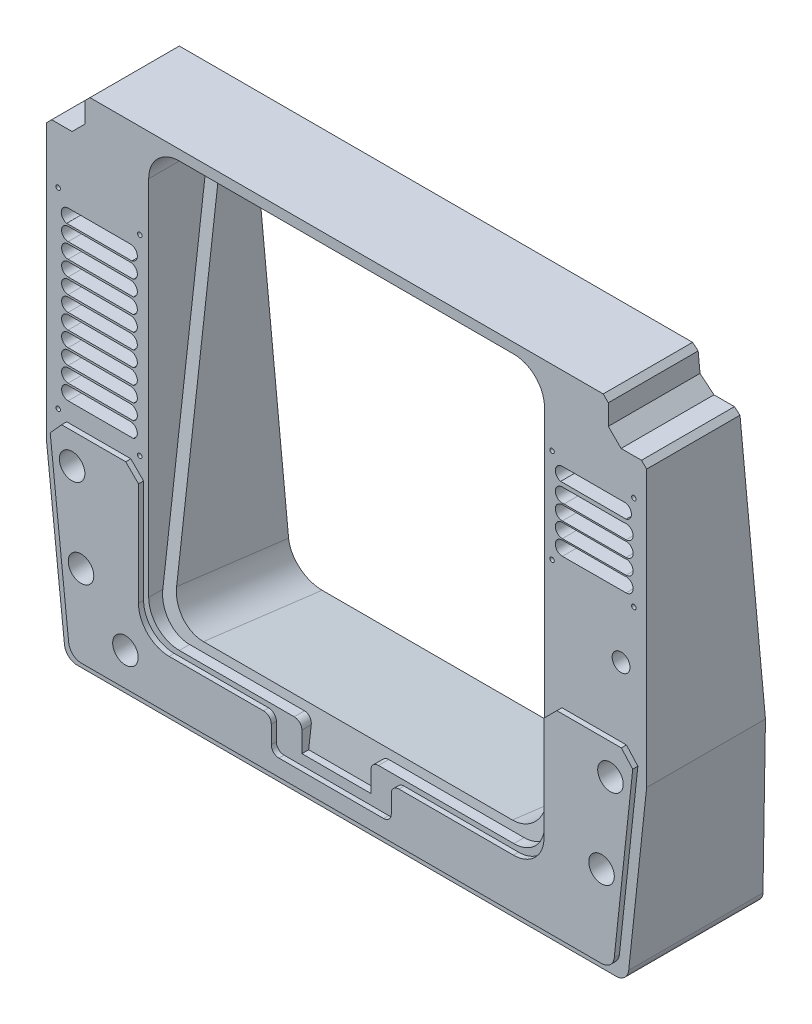
SolidWorks part; units mm, degrees
ref_plane "Front Plane" through (0, 0, 0) normal (0, 0, 1) x (1, 0, 0)
ref_plane "Top Plane" through (0, 0, 0) normal (0, 1, 0) x (1, 0, 0)
ref_plane "Right Plane" through (0, 0, 0) normal (1, 0, 0) x (0, 0, -1)
sketch "Sketch1" plane through (0, 0, 0) normal (0, 0, 1) x (1, 0, 0)
  line L0 (177.8192, -40.4681) -> (170.3192, -110.4681)
  line L1 (-40.1808, 84.5319) -> (160.8192, 84.5319)
  line L2 (-57.1808, 67.5319) -> (-57.1808, -40.4681)
  line L3 (-49.6808, -110.4681) -> (170.3192, -110.4681)
  line L4 (177.8192, 67.5319) -> (177.8192, -40.4681)
  line L5 (-57.1808, -40.4681) -> (-49.6808, -110.4681)
  line L6 (-42.1808, 74.5319) -> (-47.1808, 69.5319)
  line L8 (-42.1808, 82.5319) -> (-42.1808, 74.5319)
  line L9 (-47.1808, 69.5319) -> (-55.1808, 69.5319)
  line L13 (175.8192, 69.5319) -> (167.8192, 69.5319)
  line L14 (162.8192, 82.5319) -> (162.8192, 74.5319)
  line L15 (162.8192, 74.5319) -> (167.8192, 69.5319)
  line L16 (160.8192, 84.5319) -> (162.8192, 82.5319)
  line L17 (177.8192, 67.5319) -> (175.8192, 69.5319)
  line L18 (-55.1808, 69.5319) -> (-57.1808, 67.5319)
  line L19 (-40.1808, 84.5319) -> (-42.1808, 82.5319)
  point P1 (-42.1808, 84.5319)
  point P2 (-57.1808, 69.5319)
  point P4 (-57.1808, -40.4681)
  point P5 (177.8192, -40.4681)
  point P10 (-42.1808, 69.5319)
  point P11 (162.8192, 69.5319)
  point P12 (177.8192, 69.5319)
  point P13 (162.8192, 84.5319)
  dimension "D2" = 70
  dimension "D3" = 70
  dimension "D4" = 220
  dimension "D5" = 15
  dimension "D6" = 15
  dimension "D7" = 15
  dimension "D8" = 15
extrude "Boss-Extrude1" add sketch "Sketch1" along normal blind 53
sketch "Sketch2" plane through (0, 0, 53) normal (0, 0, 1) x (1, 0, 0)
  line L0 (160.8192, 84.5319) -> (-40.1808, 84.5319) construction
  line L1 (-5.1808, 80.5319) -> (125.8192, 80.5319)
  line L2 (-17.1808, 68.5319) -> (-17.1808, -73.4681)
  line L3 (-5.1808, -85.4681) -> (125.8192, -85.4681)
  line L4 (137.8192, 68.5319) -> (137.8192, -73.4681)
  line L5 (-57.1808, 67.5319) -> (-57.1808, -40.4681) construction
  arc A0 (-17.1808, -73.4681) -> (-5.1808, -85.4681) centre (-5.1808, -73.4681) ccw
  arc A1 (125.8192, -85.4681) -> (137.8192, -73.4681) centre (125.8192, -73.4681) ccw
  arc A2 (137.8192, 68.5319) -> (125.8192, 80.5319) centre (125.8192, 68.5319) ccw
  arc A3 (-5.1808, 80.5319) -> (-17.1808, 68.5319) centre (-5.1808, 68.5319) ccw
  point P10 (-17.1808, -85.4681)
  point P15 (137.8192, 80.5319)
  point P18 (-17.1808, 80.5319)
  dimension "D5" = 12
  dimension "D1" = 155
  dimension "D2" = 166
  dimension "D3" = 4
  dimension "D4" = 40
extrude "Cut-Extrude1" cut sketch "Sketch2" against normal blind 53
sketch "Sketch3" plane through (-17.1808, 0, 0) normal (1, 0, 0) x (0, 0, -1)
  line L0 (-50.9539, -101.3132) -> (-28, 81.8998)
  line L1 (-28, 81.8998) -> (0, 81.8998)
  line L3 (0, -101.3132) -> (-50.9539, -101.3132)
  line L4 (0, 81.8998) -> (0, -101.3132)
  dimension "D1" = 4
  dimension "D2" = 25
extrude "Boss-Extrude2" add sketch "Sketch3" along normal blind 173
sketch "Sketch4" plane through (0, 4.7194, 37.6696) normal (0, 0.1243, 0.9922) x (1, 0, 0)
  line L1 (-0.1808, 70.4051) -> (120.8192, 70.4051)
  line L2 (-12.1808, 58.4051) -> (-12.1808, -75.5949)
  line L3 (-0.1808, -87.5949) -> (120.8192, -87.5949)
  line L4 (132.8192, 58.4051) -> (132.8192, -75.5949)
  line L5 (125.8192, 76.4051) -> (-5.1808, 76.4051) construction
  line L6 (-17.1808, 61.4117) -> (-17.1808, -79.4869) construction
  arc A0 (-12.1808, 58.4051) -> (-0.1808, 70.4051) centre (-0.1808, 58.4051) cw
  arc A1 (132.8192, 58.4051) -> (120.8192, 70.4051) centre (120.8192, 58.4051) ccw
  arc A2 (120.8192, -87.5949) -> (132.8192, -75.5949) centre (120.8192, -75.5949) ccw
  arc A3 (-0.1808, -87.5949) -> (-12.1808, -75.5949) centre (-0.1808, -75.5949) cw
  point P10 (-12.1808, 70.4051)
  point P13 (132.8192, 70.4051)
  point P18 (-12.1808, -87.5949)
  dimension "D5" = 12
  dimension "D1" = 145
  dimension "D2" = 158
  dimension "D3" = 6
  dimension "D4" = 5
extrude "Cut-Extrude2" cut sketch "Sketch4" against normal blind 53
sketch "Sketch6" plane through (0, 0, 53) normal (0, 0, 1) x (1, 0, 0)
  line L0 (-5.1808, -85.4681) -> (125.8192, -85.4681) construction
  line L1 (42.8192, -85.4681) -> (69.8192, -85.4681)
  line L2 (42.8192, -85.4681) -> (42.8192, -96.4681)
  line L3 (42.8192, -96.4681) -> (69.8192, -96.4681)
  line L4 (69.8192, -85.4681) -> (69.8192, -96.4681)
  line L5 (-17.1808, 68.5319) -> (-17.1808, -73.4681) construction
  dimension "D1" = 27
  dimension "D2" = 11
  dimension "D3" = 60
extrude "Cut-Extrude3" cut sketch "Sketch6" against normal up to surface (4.0313 mm away)
fillet "Fillet1" radius 3 2 edges at (69.8192, -85.4681, 50.9844) (42.8192, -85.4681, 50.9844)
fillet "Fillet2" radius 5 2 edges at (170.3192, -110.4681, 26.5) (-49.6808, -110.4681, 26.5)
sketch "Sketch7" plane through (0, 0, 53) normal (0, 0, 1) x (1, 0, 0)
  line L0 (-53.7503, -34.9397) -> (-46.5116, -102.5008)
  line L1 (-41.54, -106.9681) -> (162.1784, -106.9681)
  line L2 (167.1499, -102.5008) -> (174.3886, -34.9397)
  line L3 (169.9213, -29.9681) -> (144.6613, -29.9681)
  line L4 (139.6613, -34.9681) -> (139.6613, -75.4681)
  line L5 (127.6613, -87.4681) -> (82.8192, -87.4681)
  line L6 (79.8192, -90.4681) -> (79.8192, -97.4681)
  line L7 (76.8192, -100.4681) -> (35.8192, -100.4681)
  line L8 (32.8192, -97.4681) -> (32.8192, -90.4681)
  line L9 (29.8192, -87.4681) -> (-7.1808, -87.4681)
  line L10 (-19.1808, -75.4681) -> (-19.1808, -34.9681)
  line L11 (-24.1808, -29.9681) -> (-49.2829, -29.9681)
  line L12 (-45.1879, -110.4681) -> (165.8263, -110.4681) construction
  line L13 (-57.1808, -40.4681) -> (-50.1595, -106.0008) construction
  line L16 (-17.1808, 68.5319) -> (-17.1808, -73.4681) construction
  line L17 (170.7978, -106.0008) -> (177.8192, -40.4681) construction
  line L18 (42.8192, -88.4681) -> (42.8192, -96.4681) construction
  line L19 (69.8192, -96.4681) -> (69.8192, -88.4681) construction
  line L20 (-49.2829, -29.9681) -> (-53.7503, -34.9397)
  line L21 (-19.1808, -34.9681) -> (-24.1808, -29.9681)
  line L22 (144.6613, -29.9681) -> (139.6613, -34.9681)
  line L23 (174.3886, -34.9397) -> (169.9213, -29.9681)
  line L25 (-5.1808, -85.4681) -> (39.8192, -85.4681) construction
  line L26 (72.8192, -85.4681) -> (125.8192, -85.4681) construction
  arc A0 (-41.54, -106.9681) -> (-46.5116, -102.5008) centre (-41.54, -101.9681) cw
  arc A1 (167.1499, -102.5008) -> (162.1784, -106.9681) centre (162.1784, -101.9681) cw
  arc A2 (-19.1808, -75.4681) -> (-7.1808, -87.4681) centre (-7.1808, -75.4681) ccw
  arc A3 (127.6613, -87.4681) -> (139.6613, -75.4681) centre (127.6613, -75.4681) ccw
  arc A4 (76.8192, -100.4681) -> (79.8192, -97.4681) centre (76.8192, -97.4681) ccw
  arc A5 (79.8192, -90.4681) -> (82.8192, -87.4681) centre (82.8192, -90.4681) cw
  arc A6 (35.8192, -100.4681) -> (32.8192, -97.4681) centre (35.8192, -97.4681) cw
  arc A7 (32.8192, -90.4681) -> (29.8192, -87.4681) centre (29.8192, -90.4681) ccw
  point P0 (-54.2829, -29.9681)
  point P4 (174.9213, -29.9681)
  point P5 (139.6613, -29.9681)
  point P12 (-19.1808, -29.9681)
  point P37 (-46.0329, -106.9681)
  point P40 (166.6713, -106.9681)
  dimension "D13" = 5
  dimension "D14" = 5
  dimension "D15" = 12
  dimension "D20" = 3
  dimension "D1" = 77
  dimension "D2" = 77
  dimension "D3" = 3.5
  dimension "D4" = 10
  dimension "D5" = 6.5
  dimension "D6" = 2
  dimension "D7" = 2
  dimension "D8" = 4
  dimension "D9" = 2
  dimension "D10" = 35.26
  dimension "D11" = 10
  dimension "D12" = 4
extrude "Boss-Extrude3" add sketch "Sketch7" along normal blind 2
sketch "Sketch15" plane through (0, 0, 0) normal (0, 0, -1) x (-1, 0, 0)
  circle A0 centre (20.6609, 47.7881) radius 0.875
  circle A1 centre (52.6329, 47.7881) radius 0.875
  circle A2 centre (20.6603, -27.217) radius 0.875
  circle A3 centre (52.6417, -27.217) radius 0.875
  circle A4 centre (-172.8186, 55.216) radius 0.875
  circle A5 centre (-140.7816, 55.216) radius 0.875
  circle A6 centre (-140.7816, 18.277) radius 0.875
  circle A7 centre (-172.8186, 18.277) radius 0.875
  dimension "D1" = 1.75
  dimension "D2" = 1.75
  dimension "D3" = 1.75
  dimension "D4" = 1.75
  dimension "D5" = 1.75
  dimension "D6" = 1.75
  dimension "D7" = 1.75
  dimension "D8" = 1.75
extrude "Cut-Extrude5" cut sketch "Sketch15" along normal blind 15 from surface at -53 starting at face at (60.3192, 21.1446, 53)
sketch "Sketch16" plane through (0, 0, 55) normal (0, 0, 1) x (1, 0, 0)
  line L0 (169.9213, -29.9681) -> (144.6613, -29.9681) construction
  line L1 (139.6613, -34.9681) -> (139.6613, -75.4681) construction
  line L2 (139.6613, -34.9681) -> (139.6613, -75.4681) construction
  line L3 (-41.54, -106.9681) -> (162.1784, -106.9681) construction
  line L4 (-53.7503, -34.9397) -> (-46.5116, -102.5008) construction
  line L5 (-19.1808, -75.4681) -> (-19.1808, -34.9681) construction
  line L6 (-24.1808, -29.9681) -> (-49.2829, -29.9681) construction
  line L7 (137.8192, -73.4681) -> (137.8192, 68.5319) construction
  circle A0 centre (162.1613, -74.9681) radius 5
  circle A1 centre (165.6613, -41.9681) radius 5
  circle A2 centre (-24.2942, -93.9681) radius 5
  circle A3 centre (-41.6808, -74.9681) radius 5
  circle A4 centre (-45.1808, -41.9681) radius 5
  circle A5 centre (167.8192, -2.9681) radius 3.5
  dimension "D3" = 10
  dimension "D6" = 10
  dimension "D9" = 10
  dimension "D14" = 10
  dimension "D15" = 10
  dimension "D18" = 7
  dimension "D1" = 45
  dimension "D2" = 22.5
  dimension "D4" = 12
  dimension "D5" = 26
  dimension "D7" = 13
  dimension "D8" = 23
  dimension "D10" = 22.5
  dimension "D11" = 45
  dimension "D12" = 26
  dimension "D13" = 12
  dimension "D16" = 30
  dimension "D17" = 27
extrude "Cut-Extrude6" cut sketch "Sketch16" against normal blind 60
sketch "Sketch17" plane through (0, 0, 53) normal (0, 0, 1) x (1, 0, 0)
  line L0 (-57.1808, 67.5319) -> (-57.1808, -40.4681) construction
  line L1 (-51.1808, 47.7819) -> (-22.1808, 47.7819)
  line L2 (-54.1808, 47.7819) -> (-54.1808, -27.2181)
  line L3 (-51.1808, -27.2181) -> (-22.1808, -27.2181)
  line L4 (-19.1808, 47.7819) -> (-19.1808, -27.2181)
  line L5 (-68.8168, 10.2819) -> (9.6258, 10.2819) construction
  line L6 (-48.6808, 36.6406) -> (-24.3739, 36.6406)
  line L7 (-48.6808, 42.7819) -> (-24.3708, 42.7819)
  line L9 (-49.2897, 37.3501) -> (-23.762, 37.3501)
  line L10 (-48.7307, 31.4236) -> (-23.1589, 31.4236)
  line L11 (-48.6808, 30.6406) -> (-24.3739, 30.6406)
  line L12 (-48.7307, 25.4236) -> (-23.1589, 25.4236)
  line L13 (-48.6808, 24.6406) -> (-24.3739, 24.6406)
  line L14 (-48.7307, 19.4236) -> (-23.1589, 19.4236)
  line L15 (-48.6808, 18.6406) -> (-24.3739, 18.6406)
  line L16 (-48.7307, 13.4236) -> (-23.1589, 13.4236)
  line L17 (-48.6808, 12.6406) -> (-24.3739, 12.6406)
  line L18 (-48.7307, 7.4236) -> (-23.1589, 7.4236)
  line L19 (-48.6808, 6.6406) -> (-24.3739, 6.6406)
  line L20 (-48.7307, 1.4236) -> (-23.1589, 1.4236)
  line L21 (-48.6808, 0.6406) -> (-24.3739, 0.6406)
  line L22 (-48.7307, -4.5764) -> (-23.1589, -4.5764)
  line L23 (-48.6808, -5.3594) -> (-24.3739, -5.3594)
  line L24 (-48.7307, -10.5764) -> (-23.1589, -10.5764)
  line L25 (-48.6808, -11.3594) -> (-24.3739, -11.3594)
  line L26 (-48.7307, -16.5764) -> (-23.1589, -16.5764)
  line L27 (-48.6837, -17.3594) -> (-24.3768, -17.3594)
  line L28 (-48.7336, -22.5764) -> (-23.1617, -22.5764)
  line L29 (144.8128, 39.542) -> (169.7853, 39.542)
  line L30 (142.3192, 55.2119) -> (171.3192, 55.2119)
  line L31 (139.3192, 55.2119) -> (139.3192, 18.2119)
  line L32 (142.3192, 18.2119) -> (172.7887, 18.2119)
  line L33 (174.3192, 55.2119) -> (174.3192, 16.7122)
  line L34 (-47.1808, 69.5319) -> (-55.1808, 69.5319) construction
  line L35 (144.8192, 51.9619) -> (169.1261, 51.9619)
  line L36 (144.1467, 46.5453) -> (169.7985, 46.5453)
  line L37 (144.8192, 44.9619) -> (169.1261, 44.9619)
  line L38 (144.7932, 44.9617) -> (169.1256, 44.9617)
  line L39 (144.8192, 38.9619) -> (169.1261, 38.9619)
  line L40 (144.7932, 38.9617) -> (169.1256, 38.9617)
  line L41 (144.8192, 32.9619) -> (169.1261, 32.9619)
  line L42 (144.7932, 32.9617) -> (169.1256, 32.9617)
  line L43 (144.8192, 26.9619) -> (169.1261, 26.9619)
  line L44 (144.7932, 26.9617) -> (169.1256, 26.9617)
  line L45 (177.8192, -40.4681) -> (177.8192, 67.5319) construction
  line L46 (169.7853, 33.542) -> (144.8192, 33.4619)
  line L47 (175.8192, 69.5319) -> (167.8192, 69.5319) construction
  line L48 (144.8192, 27.4619) -> (169.7853, 27.542)
  line L49 (144.8192, 21.4619) -> (169.7941, 21.542)
  arc A0 (-51.1808, 47.7819) -> (-54.1808, 47.7819) centre (-52.6808, 47.7819) ccw
  arc A1 (-19.1808, 47.7819) -> (-22.1808, 47.7819) centre (-20.6808, 47.7819) ccw
  arc A2 (-51.1808, -27.2181) -> (-54.1808, -27.2181) centre (-52.6808, -27.2181) cw
  arc A3 (-19.1808, -27.2181) -> (-22.1808, -27.2181) centre (-20.6808, -27.2181) cw
  arc A4 (-23.762, 37.3501) -> (-24.3708, 42.7819) centre (-24.3708, 40.0319) ccw
  arc A5 (-48.6808, 42.7819) -> (-49.2897, 37.3501) centre (-48.6808, 40.0319) ccw
  arc A6 (-23.1589, 31.4236) -> (-24.3739, 36.6406) centre (-24.3739, 33.8906) ccw
  arc A7 (-48.6808, 36.6406) -> (-48.7307, 31.4236) centre (-48.6808, 34.0319) ccw
  arc A8 (-23.1589, 25.4236) -> (-24.3739, 30.6406) centre (-24.3739, 27.8906) ccw
  arc A9 (-48.6808, 30.6406) -> (-48.7307, 25.4236) centre (-48.6808, 28.0319) ccw
  arc A10 (-23.1589, 19.4236) -> (-24.3739, 24.6406) centre (-24.3739, 21.8906) ccw
  arc A11 (-48.6808, 24.6406) -> (-48.7307, 19.4236) centre (-48.6808, 22.0319) ccw
  arc A12 (-23.1589, 13.4236) -> (-24.3739, 18.6406) centre (-24.3739, 15.8906) ccw
  arc A13 (-48.6808, 18.6406) -> (-48.7307, 13.4236) centre (-48.6808, 16.0319) ccw
  arc A14 (-23.1589, 7.4236) -> (-24.3739, 12.6406) centre (-24.3739, 9.8906) ccw
  arc A15 (-48.6808, 12.6406) -> (-48.7307, 7.4236) centre (-48.6808, 10.0319) ccw
  arc A16 (-23.1589, 1.4236) -> (-24.3739, 6.6406) centre (-24.3739, 3.8906) ccw
  arc A17 (-48.6808, 6.6406) -> (-48.7307, 1.4236) centre (-48.6808, 4.0319) ccw
  arc A18 (-23.1589, -4.5764) -> (-24.3739, 0.6406) centre (-24.3739, -2.1094) ccw
  arc A19 (-48.6808, 0.6406) -> (-48.7307, -4.5764) centre (-48.6808, -1.9681) ccw
  arc A20 (-23.1589, -10.5764) -> (-24.3739, -5.3594) centre (-24.3739, -8.1094) ccw
  arc A21 (-48.6808, -5.3594) -> (-48.7307, -10.5764) centre (-48.6808, -7.9681) ccw
  arc A22 (-23.1589, -16.5764) -> (-24.3739, -11.3594) centre (-24.3739, -14.1094) ccw
  arc A23 (-48.6808, -11.3594) -> (-48.7307, -16.5764) centre (-48.6808, -13.9681) ccw
  arc A24 (-23.1617, -22.5764) -> (-24.3768, -17.3594) centre (-24.3768, -20.1094) ccw
  arc A25 (-48.6837, -17.3594) -> (-48.7336, -22.5764) centre (-48.6837, -19.9681) ccw
  arc A26 (169.7985, 46.5453) -> (169.1261, 51.9619) centre (169.1261, 49.2119) ccw
  arc A27 (144.8192, 51.9619) -> (144.1467, 46.5453) centre (144.8192, 49.2119) ccw
  arc A36 (142.3192, 55.2119) -> (139.3192, 55.2119) centre (140.8192, 55.2119) ccw
  arc A37 (174.3192, 55.2119) -> (171.3192, 55.2119) centre (172.8192, 55.2119) ccw
  arc A38 (139.3192, 18.2119) -> (142.3192, 18.2119) centre (140.8192, 18.2119) ccw
  arc A39 (172.7887, 18.2119) -> (174.3192, 16.7122) centre (174.2887, 18.2119) ccw
  circle A40 centre (-20.6808, -27.2181) radius 0.875
  circle A41 centre (-52.6808, -27.2181) radius 0.875
  circle A42 centre (-20.6808, 47.7819) radius 0.875
  circle A43 centre (-52.6808, 47.7819) radius 0.875
  circle A44 centre (140.8192, 55.2119) radius 0.875
  circle A45 centre (172.8192, 55.2119) radius 0.875
  circle A46 centre (174.2887, 18.2119) radius 0.875
  circle A47 centre (140.8192, 18.2119) radius 0.875
  arc A49 (144.8452, 44.9617) -> (145.4783, 39.542) centre (144.8192, 42.2119) ccw
  arc A50 (144.8452, 38.9617) -> (144.8368, 33.4619) centre (144.8192, 36.2119) ccw
  arc A51 (144.8452, 32.9617) -> (144.8368, 27.4619) centre (144.8192, 30.2119) ccw
  arc A52 (144.8452, 26.9617) -> (144.8368, 21.4619) centre (144.8192, 24.2119) ccw
  arc A53 (169.7941, 21.542) -> (169.1256, 26.9617) centre (169.7853, 24.292) ccw
  arc A54 (169.7853, 27.542) -> (169.1256, 32.9617) centre (169.7853, 30.292) ccw
  arc A55 (169.7853, 33.542) -> (169.1256, 38.9617) centre (169.7853, 36.292) ccw
  arc A56 (169.7853, 39.542) -> (169.1256, 44.9617) centre (169.7853, 42.292) ccw
  dimension "D4" = 3
  dimension "D6" = 3
  dimension "D13" = 5.5
  dimension "D16" = 5.5
  dimension "D48" = 3
  dimension "D49" = 3
  dimension "D50" = 3
  dimension "D51" = 3
  dimension "D7" = 1.75
  dimension "D36" = 1.75
  dimension "D37" = 1.75
  dimension "D41" = 1.75
  dimension "D42" = 1.75
  dimension "D43" = 1.75
  dimension "D44" = 1.75
  dimension "D52" = 1.75
  dimension "D56" = 24.31
  dimension "D1" = 35
  dimension "D2" = 75
  dimension "D8" = 37.5
  dimension "D9" = 2.75
  dimension "D10" = 6
  dimension "D11" = 5
  dimension "D12" = 6
  dimension "D14" = 2.75
  dimension "D15" = 5.5
  dimension "D17" = 5.5
  dimension "6" = 6
  dimension "D18" = 5.5
  dimension "D19" = 5.5
  dimension "D20" = 5.5
  dimension "D21" = 6
  dimension "D22" = 6
  dimension "D23" = 6
  dimension "D24" = 6
  dimension "D25" = 6
  dimension "D26" = 6
  dimension "D27" = 5.5
  dimension "D28" = 5.5
  dimension "D29" = 5.5
  dimension "D30" = 5.5
  dimension "D31" = 5.5
  dimension "D32" = 6
  dimension "D33" = 5.4971
  dimension "D34" = 35
  dimension "D35" = 6
  dimension "D38" = 5.5
  dimension "D39" = 6
  dimension "D40" = 7
  dimension "D45" = 6
  dimension "D46" = 6
  dimension "D47" = 6
  dimension "D53" = 4.5
  dimension "D54" = 21.75
  dimension "D55" = 3.5
  dimension "D57" = 37
  dimension "D58" = 14.32
extrude "Cut-Extrude7" cut sketch "Sketch17" against normal blind 53
sketch "Sketch18" plane through (-57.1808, 0, 0) normal (-1, 0, 0) x (0, 0, 1)
  line L0 (53, 84.5319) -> (0, 84.5319) construction
  line L1 (18, 84.5319) -> (0, -110.4681)
  point P0 (18, 84.5319)
  dimension "D1" = 35
extrude "Cut-Extrude10" cut sketch "Sketch18" along normal through all and the other way through all flip side to cut
